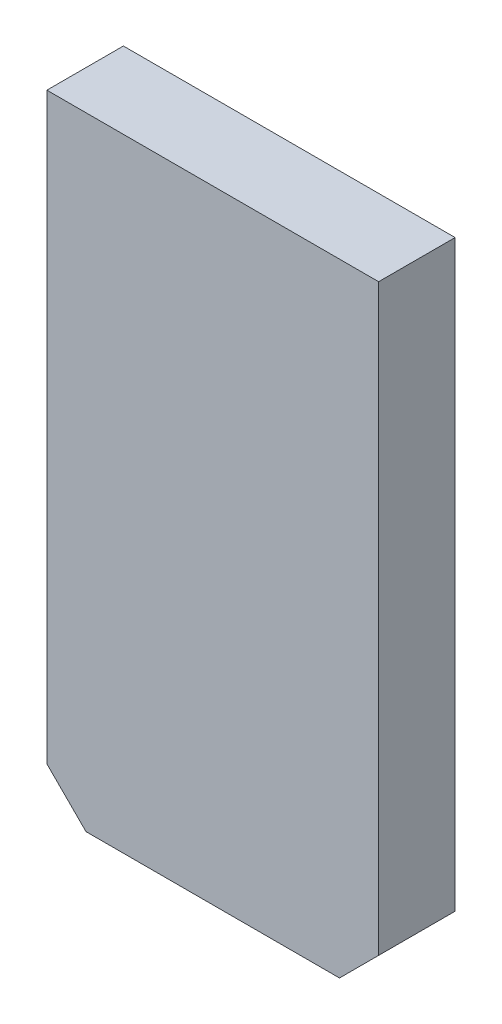
SolidWorks part; units mm, degrees
ref_plane "Front Plane" through (0, 0, 0) normal (0, 0, 1) x (1, 0, 0)
ref_plane "Top Plane" through (0, 0, 0) normal (0, 1, 0) x (1, 0, 0)
ref_plane "Right Plane" through (0, 0, 0) normal (1, 0, 0) x (0, 0, -1)
sketch "Sketch1" plane through (0, 0, 0) normal (0, 0, -1) x (-1, 0, 0)
  line L12 (-8.7386, 0.1082) -> (-5.8886, 0.1082)
  line L13 (-5.8886, 0.1082) -> (-5.4486, 0.5482)
  line L14 (-5.4486, 0.5482) -> (-5.4486, 7.1082)
  line L15 (-5.4486, 7.1082) -> (-9.1786, 7.1082)
  line L16 (-9.1786, 7.1082) -> (-9.1786, 0.5482)
  line L17 (-9.1786, 0.5482) -> (-8.7386, 0.1082)
  point P2 (-7.3136, 0.1082)
  point P4 (0, 0)
  point P6 (-7.3136, 0.1082)
  point P8 (0, 0)
  dimension "D1" = 7
  dimension "D2" = 3.73
  dimension "D3" = 2.85
  dimension "D4" = 0.44
  dimension "D5" = 45
  dimension "D6" = 45
  dimension "D7" = 0.44
extrude "Boss-Extrude1" add sketch "Sketch1" along normal blind 0.86
